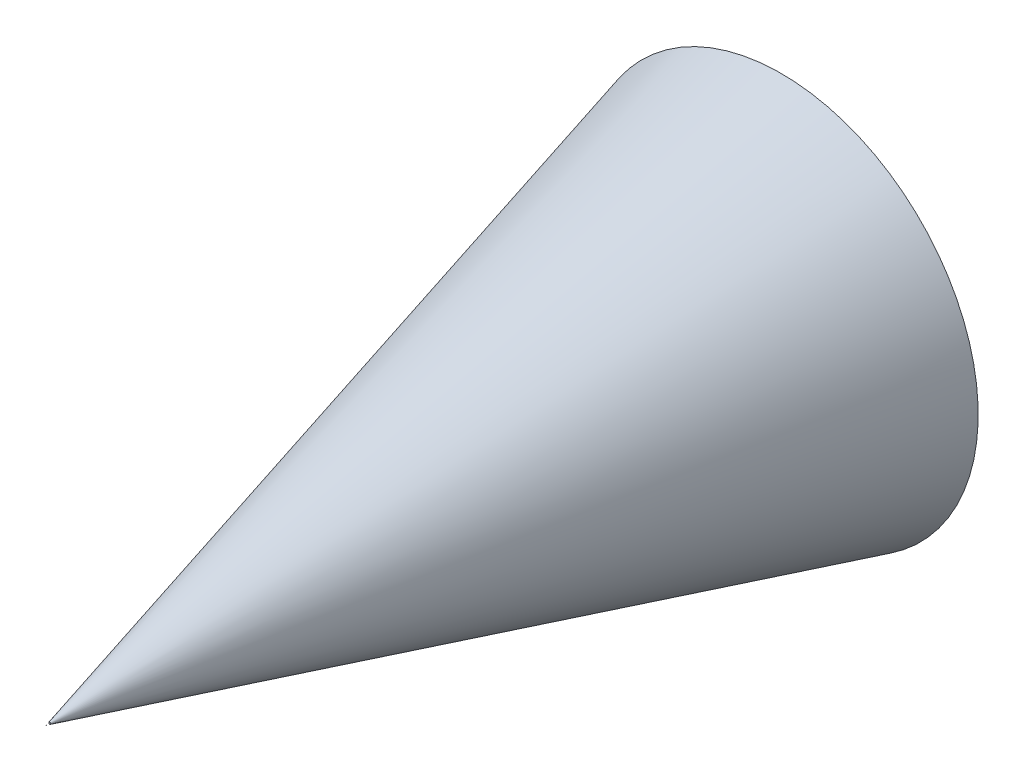
SolidWorks part; units mm, degrees
ref_plane "Front Plane" through (0, 0, 0) normal (0, 0, 1) x (1, 0, 0)
ref_plane "Top Plane" through (0, 0, 0) normal (0, 1, 0) x (1, 0, 0)
ref_plane "Right Plane" through (0, 0, 0) normal (1, 0, 0) x (0, 0, -1)
sketch "Sketch1" plane through (0, 0, 0) normal (0, 1, 0) x (1, 0, 0)
  line L0 (0, 0) -> (0, 4000)
  line L1 (0, 4000) -> (1071.7968, 4000)
  line L2 (1071.7968, 4000) -> (0, 0)
  dimension "D1" = 15
  dimension "D2" = 4000
revolve "Revolve1" add sketch "Sketch1" angle 360 about L0
sketch "Sketch2" plane through (0, 0, 0) normal (1, 0, 0) x (0, 0, -1)
  line L0 (0, 0) -> (20, -5.359)
  line L1 (0, 0) -> (4000, -1071.7968) construction
  line L2 (20, -5.359) -> (20, 5.359)
  line L3 (4000, 1071.7968) -> (0, 0) construction
  line L4 (20, 5.359) -> (0, 0)
  dimension "D1" = 20
extrude "Cut-Extrude1" cut sketch "Sketch2" against normal through all both and the other way through all
sketch "Sketch4" plane through (0, 0, 0) normal (0, 0, 1) x (1, 0, 0)
  line L1 (-0.5, 0.5) -> (0.5, 0.5)
  line L2 (-0.5, 0.5) -> (-0.5, -0.5)
  line L3 (-0.5, -0.5) -> (0.5, -0.5)
  line L4 (0.5, 0.5) -> (0.5, -0.5)
  line L5 (-0.5, 0.5) -> (0.5, -0.5) construction
  line L6 (-0.5, -0.5) -> (0.5, 0.5) construction
  point P0 (0, 0)
  dimension "D1" = 1
extrude "Boss-Extrude1" add sketch "Sketch4" against normal blind 1 separate body
